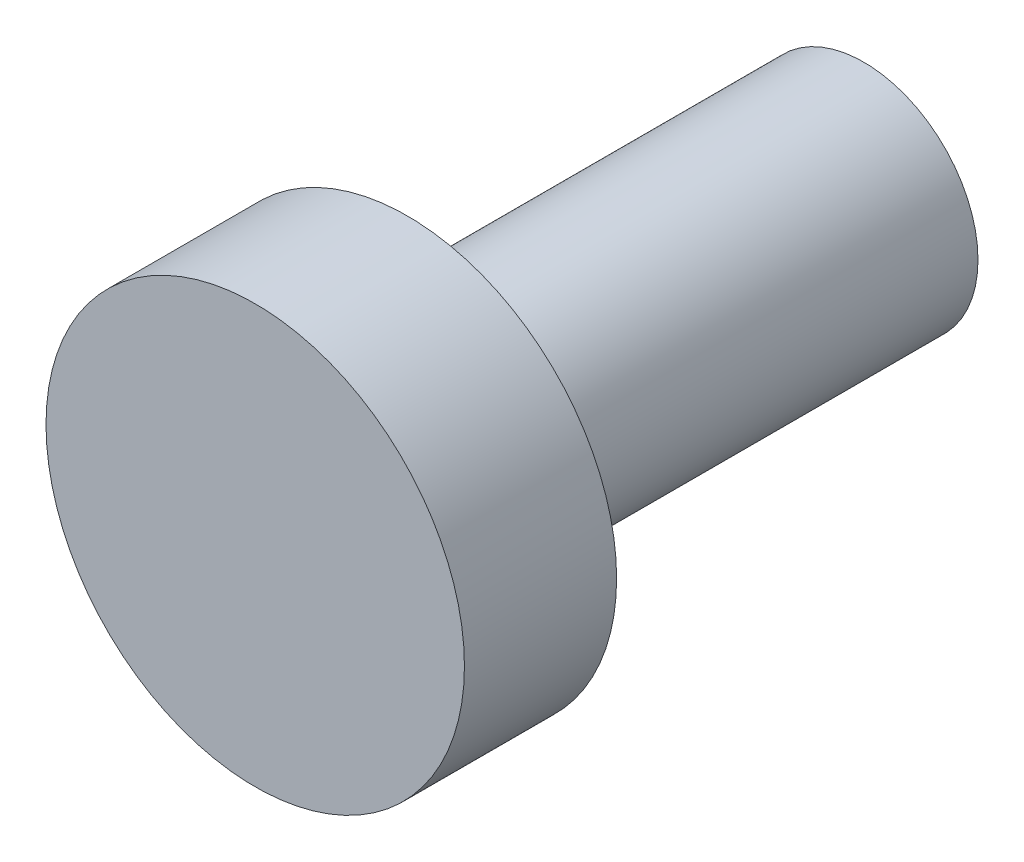
SolidWorks part; units mm, degrees
ref_plane "前视基准面" through (0, 0, 0) normal (0, 0, 1) x (1, 0, 0)
ref_plane "上视基准面" through (0, 0, 0) normal (0, 1, 0) x (1, 0, 0)
ref_plane "右视基准面" through (0, 0, 0) normal (1, 0, 0) x (0, 0, -1)
sketch "草图1" plane through (0, 0, 0) normal (0, 0, 1) x (1, 0, 0)
  circle A0 centre (0, 0) radius 1.5
  dimension "D1" = 3
extrude "M3螺杆_牙型简化" add sketch "草图1" along normal blind 6 from offset 6
sketch "草图2" plane through (0, 0, 0) normal (0, 0, 1) x (1, 0, 0)
  circle A0 centre (0, 0) radius 2.75
  dimension "D1" = 5.5
extrude "圆柱头_直径5.5" add sketch "草图2" along normal blind 2
